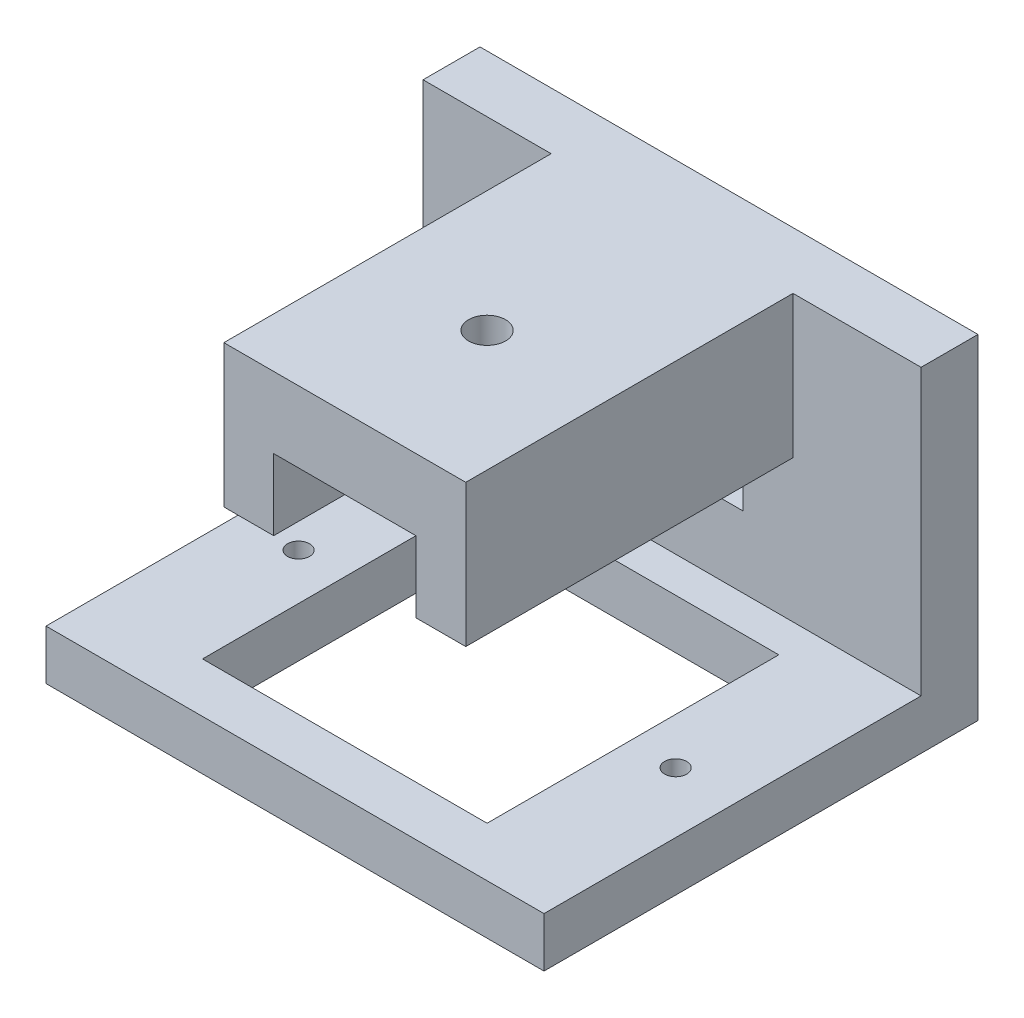
SolidWorks part; units mm, degrees
other "Markup1"
sketch "Sketch3" plane through (70, 5, 0) normal (0.0596, 0.7618, 0.645) x (0.9973, -0.0727, -0.0062)
material "ABS"
ref_plane "Front Plane" through (0, 0, 0) normal (0, 0, 1) x (1, 0, 0)
ref_plane "Top Plane" through (0, 0, 0) normal (0, 1, 0) x (1, 0, 0)
ref_plane "Right Plane" through (0, 0, 0) normal (1, 0, 0) x (0, 0, -1)
sketch "Sketch1" plane through (0, 0, 0) normal (0, 1, 0) x (1, 0, 0)
  line L1 (0, 0) -> (70, 0)
  line L2 (0, 0) -> (0, 54)
  line L3 (0, 54) -> (70, 54)
  line L4 (70, 0) -> (70, 54)
  line L5 (15, 0) -> (55, 0)
  line L6 (15, 0) -> (15, 41)
  line L7 (15, 41) -> (55, 41)
  line L8 (55, 0) -> (55, 41)
  dimension "D1" = 70
  dimension "D2" = 54
  dimension "D3" = 40
  dimension "D4" = 41
  dimension "D5" = 15
extrude "Boss-Extrude1" add sketch "Sketch1" along normal blind 7 contours L8 L1 L4 L3 L2 L6 L7
sketch "Sketch4" plane through (0, 7, 0) normal (0, 1, 0) x (1, 0, 0)
  line L1 (0, 0) -> (0, 54) construction
  line L3 (0, 0) -> (15, 0) construction
  circle A0 centre (8.5, 20) radius 1.55
  circle A1 centre (61.5, 20) radius 1.55
  dimension "D1" = 3.1
  dimension "D2" = 8.5
  dimension "D3" = 20
  dimension "D4" = 53
extrude "Cut-Extrude1" cut sketch "Sketch4" against normal through all
sketch "Sketch5" plane through (0, 7, 0) normal (0, 1, 0) x (1, 0, 0)
  line L0 (70, 0) -> (70, 54) construction
  line L1 (0, 54) -> (70, 54)
  line L2 (0, 54) -> (0, 46)
  line L3 (0, 46) -> (70, 46)
  line L4 (70, 54) -> (70, 46)
  dimension "D1" = 8
extrude "Boss-Extrude2" add sketch "Sketch5" along normal blind 40
sketch "Sketch6" plane through (0, 0, -54) normal (0, 0, -1) x (-1, 0, 0)
  line L0 (-70, 47) -> (-70, 0) construction
  line L1 (-45, 37) -> (-25, 37)
  line L2 (-45, 37) -> (-45, 17)
  line L3 (-45, 17) -> (-25, 17)
  line L4 (-25, 37) -> (-25, 17)
  line L6 (-70, 47) -> (0, 47) construction
  dimension "D1" = 20
  dimension "D2" = 20
  dimension "D3" = 25
  dimension "D4" = 10
extrude "Cut-Extrude2" cut sketch "Sketch6" against normal through all
sketch "Sketch8" plane through (0, 0, -46) normal (0, 0, 1) x (1, 0, 0)
  line L0 (18, 47) -> (52, 47)
  line L1 (0, 47) -> (70, 47) construction
  line L2 (52, 47) -> (52, 27)
  line L3 (52, 27) -> (45, 27)
  line L4 (45, 37) -> (45, 17) construction
  line L5 (45, 27) -> (45, 37)
  line L6 (25, 37) -> (45, 37) construction
  line L7 (45, 37) -> (25, 37)
  line L8 (25, 37) -> (25, 27)
  line L9 (25, 17) -> (25, 37) construction
  line L10 (25, 27) -> (18, 27)
  line L11 (18, 27) -> (18, 47)
  dimension "D1" = 20
  dimension "D2" = 7
extrude "Boss-Extrude4" add sketch "Sketch8" along normal blind 46
sketch "Sketch9" plane through (0, 47, 0) normal (0, 1, 0) x (1, 0, 0)
  line L0 (52, 0) -> (18, 0) construction
  line L1 (18, 0) -> (18, 46) construction
  circle A0 centre (35, 20) radius 2.6
  dimension "D1" = 20
  dimension "D3" = 5.2
  dimension "D2" = 17
extrude "Cut-Extrude3" cut sketch "Sketch9" against normal through all
sketch "Sketch10" plane through (0, 0, 0) normal (0, 0, 1) x (1, 0, 0)
  line L1 (0, 7) -> (70, 7)
  line L2 (0, 7) -> (0, 0)
  line L3 (0, 0) -> (70, 0)
  line L4 (70, 7) -> (70, 0)
extrude "Boss-Extrude5" add sketch "Sketch10" along normal blind 7
